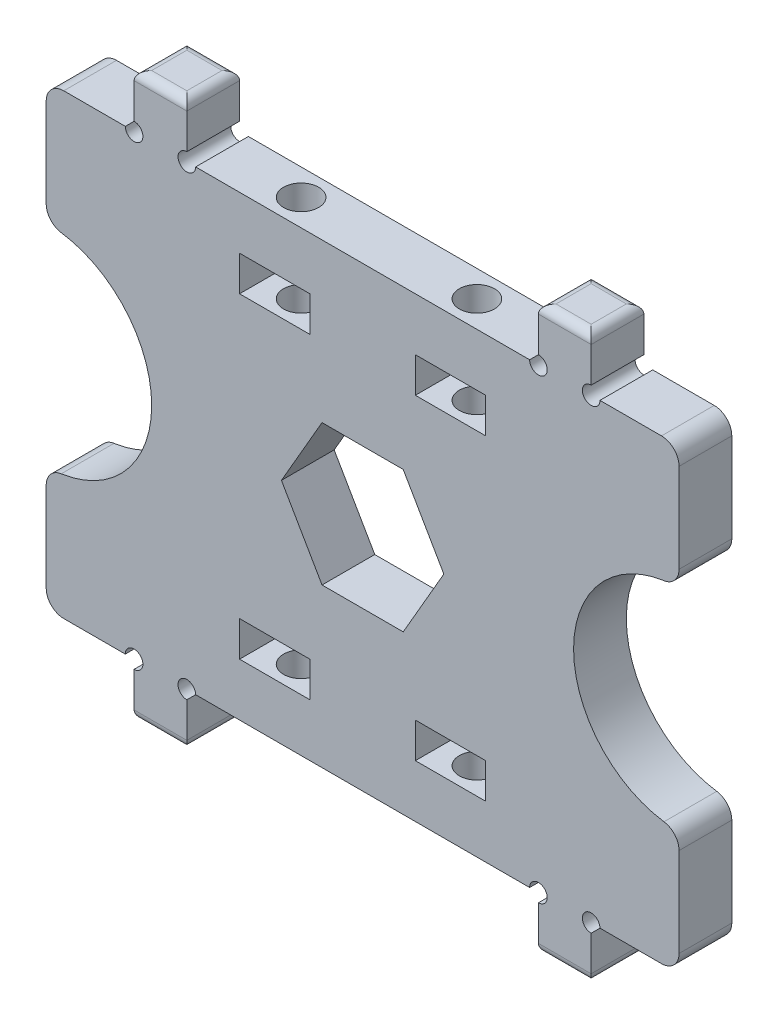
SolidWorks part; units mm, degrees
ref_plane "Front Plane" through (0, 0, 0) normal (0, 0, 1) x (1, 0, 0)
ref_plane "Top Plane" through (0, 0, 0) normal (0, 1, 0) x (1, 0, 0)
ref_plane "Right Plane" through (0, 0, 0) normal (1, 0, 0) x (0, 0, -1)
sketch "Sketch1" plane through (0, 0, 0) normal (0, 0, 1) x (1, 0, 0)
  line L1 (0, 0) -> (9.5, 0)
  line L2 (0, 0) -> (0, 9)
  line L6 (10, -0.5) -> (10, -3)
  line L7 (10, -3) -> (13, -3)
  line L8 (13, -0.5) -> (13, -3)
  line L9 (3, 5) -> (7, 5)
  line L10 (3, 5) -> (3, 3)
  line L11 (3, 3) -> (7, 3)
  line L12 (7, 5) -> (7, 3)
  line L13 (13.5, 0) -> (18, 0)
  line L14 (0, 0) -> (10.5, 0)
  line L15 (0, 0) -> (0, 13)
  line L16 (4.6188, 13) -> (12, 13)
  line L17 (18, 0) -> (18, 7)
  line L23 (0, 9) -> (2.3094, 9)
  line L24 (2.3094, 9) -> (4.6188, 13)
  line L25 (-2.3094, 17) -> (-3.4641, 15) [skipped]
  line L26 (-4.6188, 13) -> (-3.4641, 11) [skipped]
  line L27 (2.3094, 17) -> (0, 17) [skipped]
  line L28 (4.6188, 13) -> (3.4641, 15) [skipped]
  arc A0 (13.5, 0) -> (13, -0.5) centre (13, 0) ccw
  arc A1 (10, -0.5) -> (9.5, 0) centre (10, 0) ccw
  circle A3 centre (0, 13) radius 4 construction
  arc A4 (12, 13) -> (18, 7) centre (18, 13) ccw
  point P13 (5, 3)
  dimension "D1" = 13
  dimension "D2" = 18
  dimension "D3" = 10
  dimension "D4" = 3
  dimension "D5" = 3
  dimension "D6" = 5
  dimension "D7" = 4
  dimension "D8" = 2
  dimension "D9" = 3
extrude "Boss-Extrude1" add sketch "Sketch1" along normal blind 3 contours A4 L16 L24 L23 L2 L1 A1 L6 L7 L8 A0 L13 L17 L9 L12 L11 L10
sketch "Sketch2" plane through (0, 0, 0) normal (0, -1, 0) x (1, 0, 0)
  line L1 (0, 3) -> (0, 0) construction
  line L2 (0, 3) -> (9.5, 3) construction
  circle A0 centre (5, 1.5) radius 1
  dimension "D1" = 1.5
  dimension "D2" = 5
extrude "Cut-Extrude1" cut sketch "Sketch2" against normal blind 8 contours A0
fillet "Fillet1" radius 1 2 edges at (18, 7, 1.5) (18, 0, 1.5)
fillet "Fillet2" radius 0.5 4 edges at (10, -3, 1.5) (13, -3, 1.5) (11.5, -3, 0) (11.5, -3, 3)
mirror "Mirror1" about plane through (0, 0, 3) normal (-1, 0, 0) of bodies 102
mirror "Mirror2" about plane through (0, 13, 3) normal (0, 1, 0) of bodies 103
